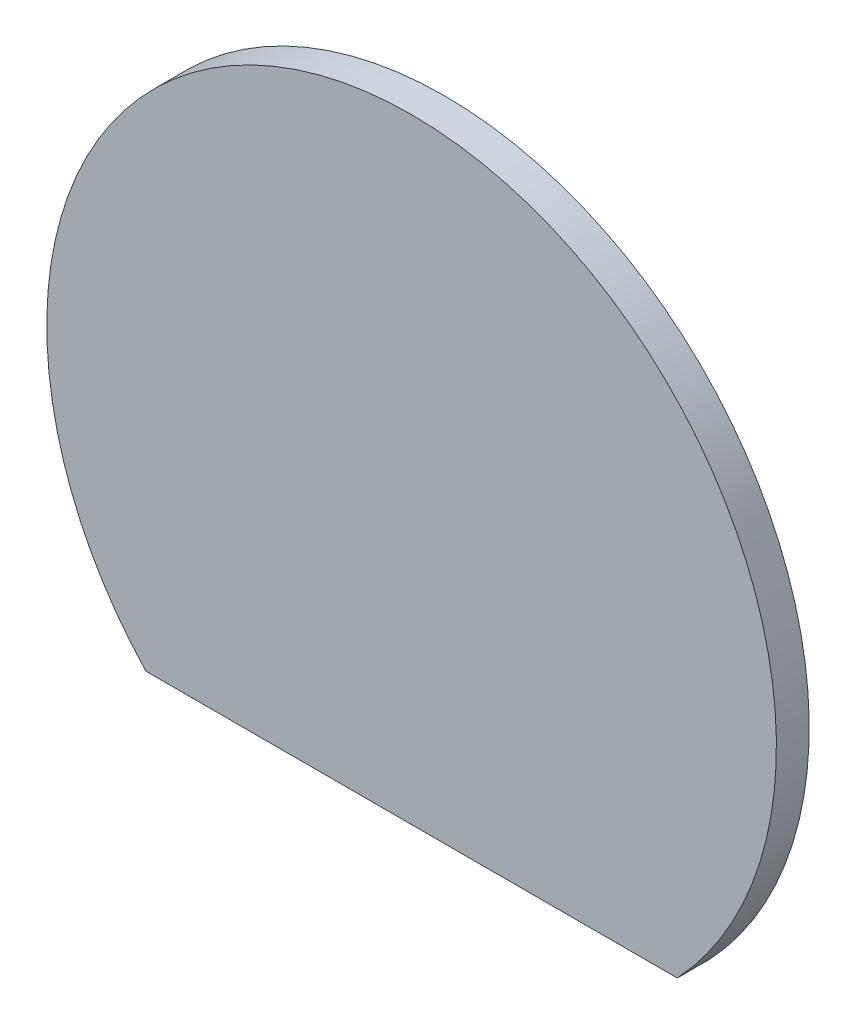
SolidWorks part; units mm, degrees
ref_plane "Plan de face" through (0, 0, 0) normal (0, 0, 1) x (1, 0, 0)
ref_plane "Plan de dessus" through (0, 0, 0) normal (0, 1, 0) x (1, 0, 0)
ref_plane "Plan de droite" through (0, 0, 0) normal (1, 0, 0) x (0, 0, -1)
sketch "Contour" plane through (0, 0, 0) normal (0, 0, 1) x (1, 0, 0)
  line L0 (0, 17.8) -> (0, -12.2) construction
  line L1 (0, -55) -> (0, 55) construction
  line L2 (-12.9615, -12.2) -> (12.9615, -12.2)
  arc A0 (12.9615, -12.2) -> (-12.9615, -12.2) centre (0, 0) ccw
  dimension "D1" = 35.6
  dimension "D2" = 30
extrude "Boss.-Extru.1_Contour" add sketch "Contour" along normal blind 1.6
